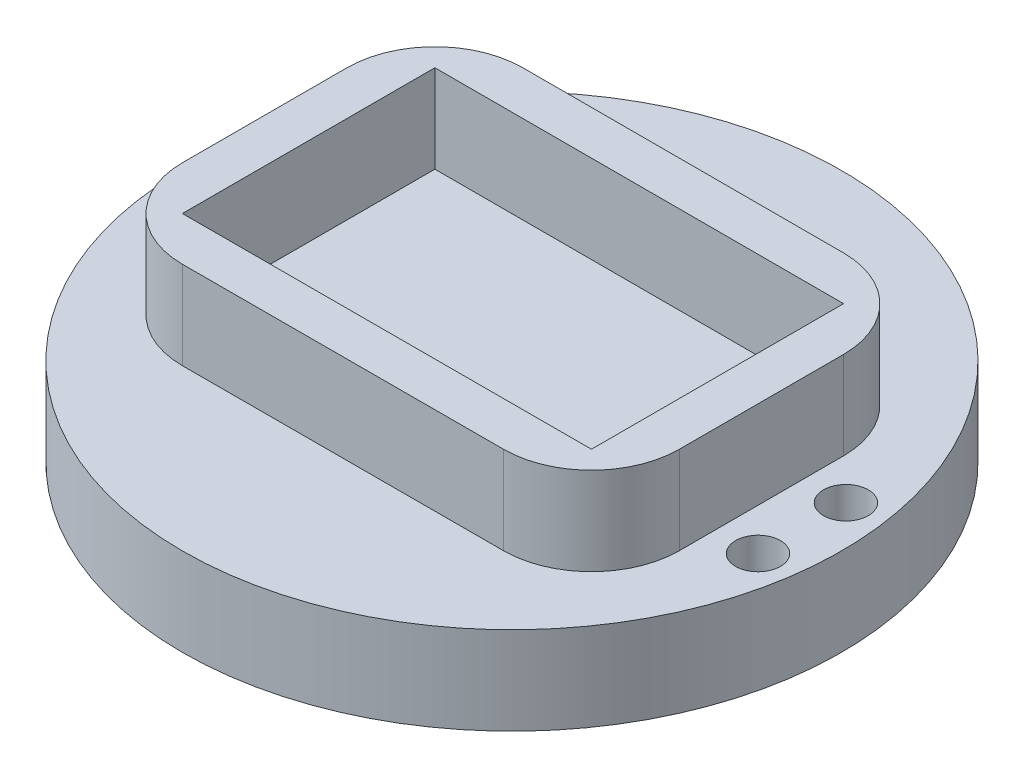
SolidWorks part; units mm, degrees
ref_plane "Front Plane" through (0, 0, 0) normal (0, 0, 1) x (1, 0, 0)
ref_plane "Top Plane" through (0, 0, 0) normal (0, 1, 0) x (1, 0, 0)
ref_plane "Right Plane" through (0, 0, 0) normal (1, 0, 0) x (0, 0, -1)
sketch "Sketch1" plane through (0, 0, 0) normal (0, 1, 0) x (1, 0, 0)
  circle A0 centre (11.9455, 0) radius 37.5
  dimension "D1" = 75
extrude "Boss-Extrude1" add sketch "Sketch1" along normal blind 10
sketch "Sketch2" plane through (0, 0, 0) normal (0, 1, 0) x (1, 0, 0)
  line L4 (-11.3045, -14.25) -> (35.1955, -14.2)
  line L5 (84.5, -14.2) -> (86.9, -14.2) construction
  line L6 (35.1955, -14.2) -> (35.1955, 14.4843)
  line L7 (-11.3045, 14.4843) -> (-11.3045, -14.25)
  line L8 (-11.3045, 14.4843) -> (35.1955, 14.4843)
  line L9 (-6.3045, 19.4843) -> (30.1955, 19.4843)
  line L10 (40.1955, -9.2054) -> (40.1955, 9.4843)
  line L11 (-6.2937, -19.2446) -> (30.2063, -19.2054)
  line L12 (-16.3045, 9.4843) -> (-16.3045, -9.2446)
  line L13 (-16.3045, -19.2554) -> (40.1955, -19.1946) construction
  line L14 (-16.3045, 19.4843) -> (-16.3045, -19.2554) construction
  line L15 (40.1955, -19.1946) -> (40.1955, 19.4843) construction
  line L16 (-16.3045, 19.4843) -> (40.1955, 19.4843) construction
  arc A2 (-6.2937, -19.2446) -> (-16.3045, -9.2446) centre (-6.3045, -9.2446) cw
  arc A3 (40.1955, -9.2054) -> (30.2063, -19.2054) centre (30.1955, -9.2054) cw
  arc A4 (30.1955, 19.4843) -> (40.1955, 9.4843) centre (30.1955, 9.4843) cw
  arc A5 (-6.3045, 19.4843) -> (-16.3045, 9.4843) centre (-6.3045, 9.4843) ccw
  dimension "D2" = 10
  dimension "D1" = 5
extrude "Boss-Extrude2" add sketch "Sketch2" along normal blind 10 from offset 10
sketch "Sketch3" plane through (0, 10, 0) normal (0, 1, 0) x (1, 0, 0)
  line L0 (11.9455, 37.5) -> (11.9455, 0) construction
  line L1 (11.9455, 0) -> (-21.0545, 0) construction
  line L2 (-21.0545, 0) -> (-21.0545, -5) construction
  circle A0 centre (11.9455, 0) radius 37.5 construction
  circle A1 centre (-21.0545, -5) radius 2.55
  circle A2 centre (-21.0545, 5) radius 2.55
  circle A3 centre (44.9455, -5) radius 2.55
  circle A4 centre (44.9455, 5) radius 2.55
  dimension "D3" = 5.1
  dimension "D1" = 33
  dimension "D2" = 5
extrude "Cut-Extrude1" cut sketch "Sketch3" against normal blind 10
